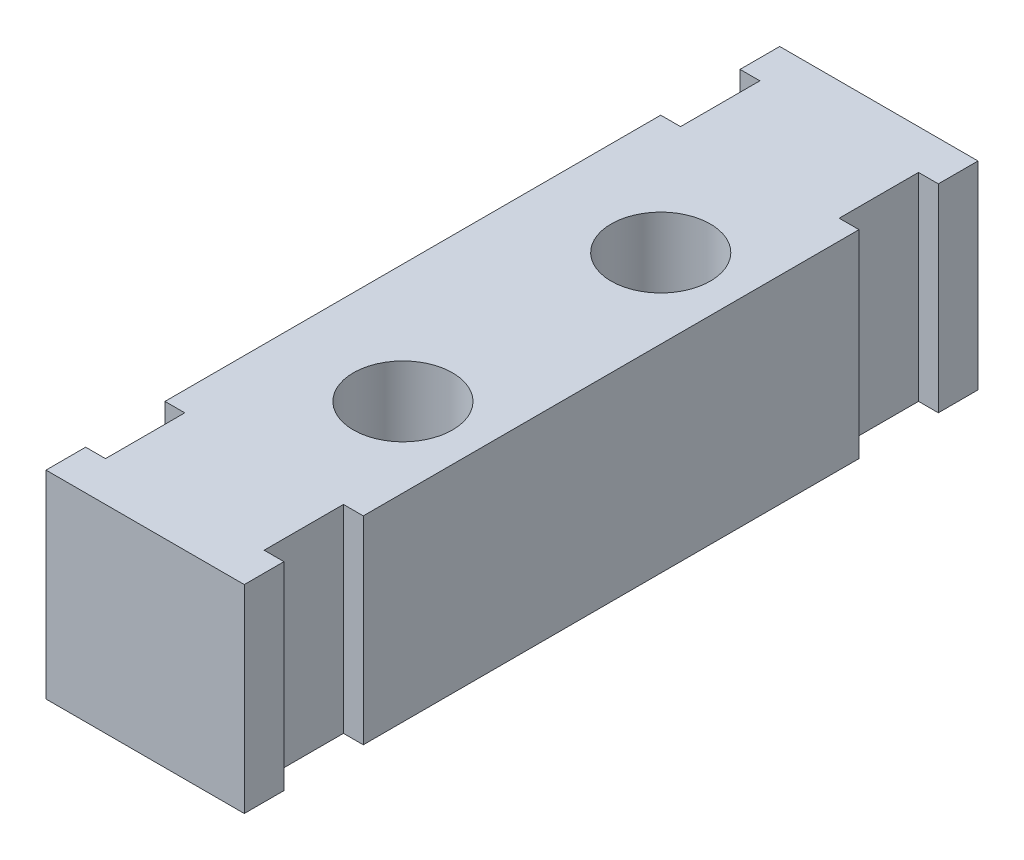
SolidWorks part; units mm, degrees
ref_plane "Alzado" through (0, 0, 0) normal (0, 0, 1) x (1, 0, 0)
ref_plane "Planta" through (0, 0, 0) normal (0, 1, 0) x (1, 0, 0)
ref_plane "Vista lateral" through (0, 0, 0) normal (1, 0, 0) x (0, 0, -1)
sketch "Croquis1" plane through (0, 0, 0) normal (0, 0, 1) x (1, 0, 0)
  line L1 (-5, -5) -> (5, -5)
  line L2 (-5, -5) -> (-5, 5)
  line L3 (-5, 5) -> (5, 5)
  line L4 (5, -5) -> (5, 5)
  line L5 (-5, -5) -> (5, 5) construction
  line L6 (-5, 5) -> (5, -5) construction
  point P0 (0, 0)
  dimension "D1" = 10
  dimension "D2" = 10
extrude "Saliente-Extruir1" add sketch "Croquis1" along normal blind 37
sketch "Croquis2" plane through (0, 5, 0) normal (0, 1, 0) x (1, 0, 0)
  line L0 (1, 0) -> (1, -37) construction
  line L1 (5, 0) -> (-5, 0) construction
  line L2 (5, -37) -> (-5, -37) construction
  line L3 (5, -37) -> (5, 0) construction
  circle A0 centre (1, -12) radius 2.5
  circle A1 centre (1, -25) radius 2.5
  dimension "D1" = 5
  dimension "D2" = 5
  dimension "D3" = 12
  dimension "D4" = 12
  dimension "D5" = 4
extrude "Cortar-Extruir1" cut sketch "Croquis2" against normal through all
sketch "Croquis4" plane through (0, 5, 0) normal (0, 1, 0) x (1, 0, 0)
  line L0 (-5, -37) -> (-5, 0) construction
  line L1 (-5, -35) -> (-4, -35)
  line L2 (-5, -35) -> (-5, -31)
  line L3 (-5, -31) -> (-4, -31)
  line L4 (-4, -35) -> (-4, -31)
  line L5 (5, -37) -> (-5, -37) construction
  line L6 (5, -37) -> (5, 0) construction
  line L7 (5, -35) -> (4, -35)
  line L8 (5, -35) -> (5, -31)
  line L9 (5, -31) -> (4, -31)
  line L10 (4, -35) -> (4, -31)
  line L11 (5, 0) -> (-5, 0) construction
  line L12 (5, -6) -> (4, -6)
  line L13 (5, -6) -> (5, -2)
  line L14 (5, -2) -> (4, -2)
  line L15 (4, -6) -> (4, -2)
  line L16 (-5, -6) -> (-4, -6)
  line L17 (-5, -6) -> (-5, -2)
  line L18 (-5, -2) -> (-4, -2)
  line L19 (-4, -6) -> (-4, -2)
  dimension "D1" = 4
  dimension "D2" = 1
  dimension "D3" = 2
  dimension "D4" = 4
  dimension "D5" = 1
  dimension "D6" = 2
  dimension "D7" = 1
  dimension "D8" = 4
  dimension "D9" = 2
  dimension "D10" = 4
  dimension "D11" = 1
  dimension "D12" = 2
extrude "Cortar-Extruir2" cut sketch "Croquis4" against normal through all
